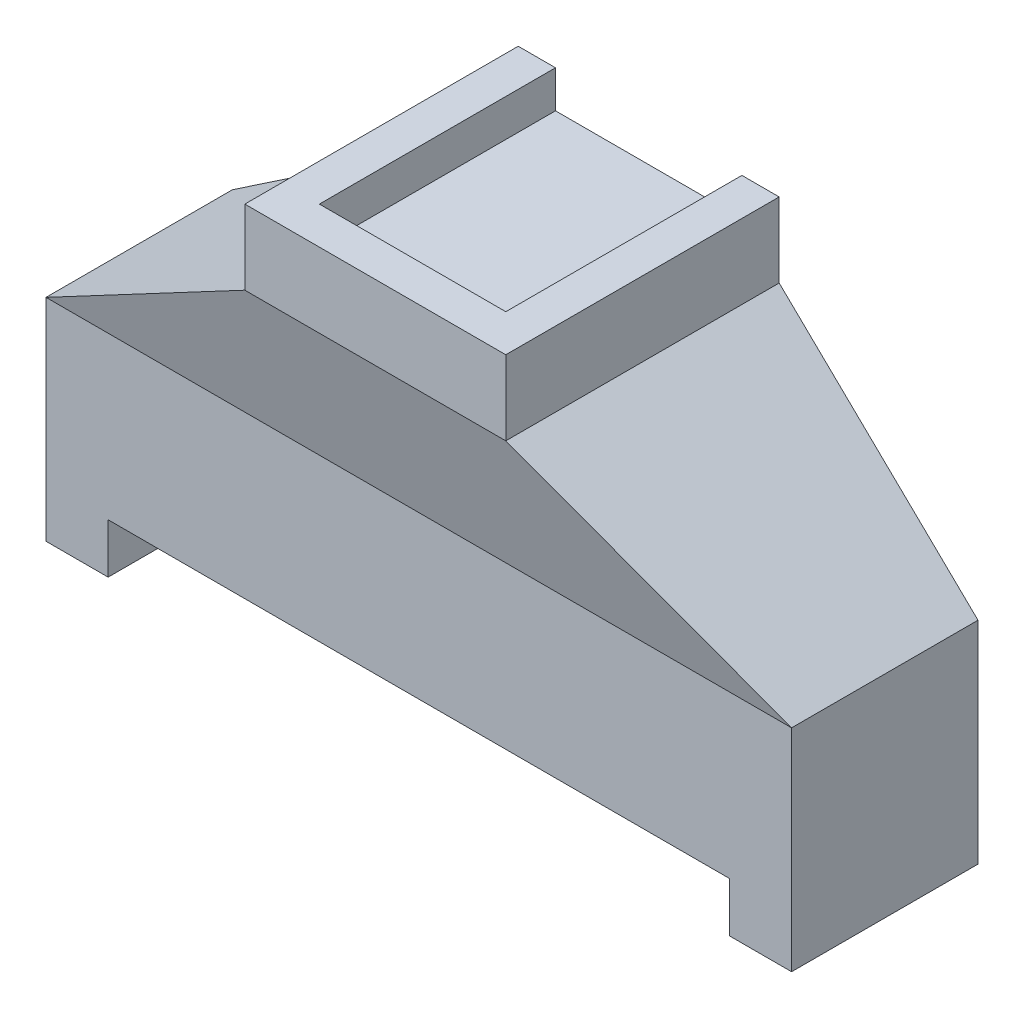
SolidWorks part; units mm, degrees
ref_plane "Front Plane" through (0, 0, 0) normal (0, 0, 1) x (1, 0, 0)
ref_plane "Top Plane" through (0, 0, 0) normal (0, 1, 0) x (1, 0, 0)
ref_plane "Right Plane" through (0, 0, 0) normal (1, 0, 0) x (0, 0, -1)
sketch "Sketch1" plane through (0, 0, 0) normal (0, 1, 0) x (1, 0, 0)
  line L1 (-30, -7.5) -> (30, -7.5)
  line L2 (-30, -7.5) -> (-30, 7.5)
  line L3 (-30, 7.5) -> (30, 7.5)
  line L4 (30, -7.5) -> (30, 7.5)
  line L5 (-30, -7.5) -> (30, 7.5) construction
  line L6 (-30, 7.5) -> (30, -7.5) construction
  point P0 (0, 0)
  dimension "D1" = 60
  dimension "D2" = 15
extrude "Boss-Extrude1" add sketch "Sketch1" along normal blind 13
sketch "Sketch4" plane through (0, 0, 0) normal (0, -1, 0) x (-1, 0, 0)
  line L0 (-30, 7.5) -> (30, 7.5) construction
  line L1 (30, -7.5) -> (25, -7.5)
  line L2 (30, -7.5) -> (30, 7.5)
  line L3 (30, 7.5) -> (25, 7.5)
  line L4 (25, -7.5) -> (25, 7.5)
  dimension "D1" = 5
extrude "Boss-Extrude2" add sketch "Sketch4" along normal blind 4
mirror "Mirror1" about plane through (0, 0, 0) normal (1, 0, 0) of "Boss-Extrude2"
ref_plane "Plane1" through (0, 28, 0) normal (0, -1, 0) x (-1, 0, 0)
sketch "Sketch5" plane through (0, 28, 0) normal (0, -1, 0) x (-1, 0, 0)
  line L1 (10.5, -11) -> (-10.5, -11)
  line L2 (10.5, -11) -> (10.5, 11)
  line L3 (10.5, 11) -> (-10.5, 11)
  line L4 (-10.5, -11) -> (-10.5, 11)
  line L5 (10.5, -11) -> (-10.5, 11) construction
  line L6 (10.5, 11) -> (-10.5, -11) construction
  point P0 (0, 0)
  dimension "D1" = 21
  dimension "D2" = 22
extrude "Boss-Extrude3" add sketch "Sketch5" along normal blind 3 separate body
loft "Loft1" add section face at (0, 13, 0) section face at (0, 25, 0)
sketch "Sketch7" plane through (0, 28, 0) normal (0, -1, 0) x (-1, 0, 0)
  line L0 (10.5, 11) -> (7.5, 11)
  line L1 (10.5, 11) -> (-10.5, 11) construction
  line L2 (7.5, 11) -> (7.5, -8)
  line L3 (7.5, -8) -> (-7.5, -8)
  line L4 (-7.5, -8) -> (-7.5, 11)
  line L5 (-7.5, 11) -> (-10.5, 11)
  line L6 (-10.5, 11) -> (-10.5, -11)
  line L7 (-10.5, -11) -> (10.5, -11)
  line L8 (10.5, -11) -> (10.5, 11)
  dimension "D1" = 3
  dimension "D2" = 3
  dimension "D3" = 3
extrude "Boss-Extrude4" add sketch "Sketch7" against normal blind 3
